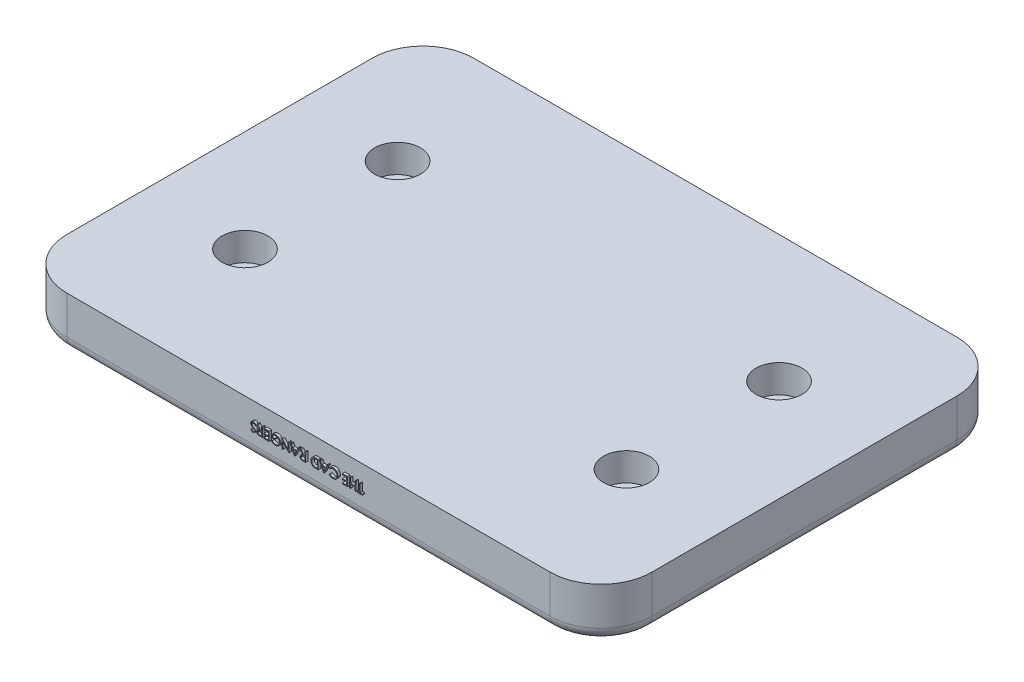
SolidWorks part; units mm, degrees
ref_plane "Front Plane" through (0, 0, 0) normal (0, 0, 1) x (1, 0, 0)
ref_plane "Top Plane" through (0, 0, 0) normal (0, 1, 0) x (1, 0, 0)
ref_plane "Right Plane" through (0, 0, 0) normal (1, 0, 0) x (0, 0, -1)
sketch "Sketch1" plane through (0, 0, 0) normal (0, 1, 0) x (1, 0, 0)
  line L0 (0, 125.2343) -> (0, -131.8583) construction
  line L1 (-95, -80) -> (95, -80)
  line L2 (-115, -60) -> (-115, 60)
  line L3 (-95, 80) -> (95, 80)
  line L4 (115, -60) -> (115, 60)
  line L5 (-115, -80) -> (115, 80) construction
  line L6 (-115, 80) -> (115, -80) construction
  line L7 (-168.0583, 0) -> (157.758, 0) construction
  arc A0 (95, 80) -> (115, 60) centre (95, 60) cw
  arc A1 (95, -80) -> (115, -60) centre (95, -60) ccw
  arc A2 (-95, -80) -> (-115, -60) centre (-95, -60) cw
  arc A3 (-115, 60) -> (-95, 80) centre (-95, 60) cw
  point P0 (0, 0)
  dimension "D3" = 20
  dimension "D1" = 160
  dimension "D2" = 230
extrude "Boss-Extrude1" add sketch "Sketch1" along normal blind 20
sketch "Sketch2" plane through (0, 0, 0) normal (0, -1, 0) x (1, 0, 0)
  line L0 (-115, 0) -> (138.7275, 0) construction
  line L1 (-115, -60) -> (-115, 60) construction
  line L3 (0, 55.4662) -> (0, -57.4516) construction
  circle A0 centre (-75, 30) radius 5.5
  circle A1 centre (75, 30) radius 5.5
  circle A2 centre (75, -30) radius 5.5
  circle A3 centre (-75, -30) radius 5.5
  dimension "D1" = 11
  dimension "D2" = 75
  dimension "D3" = 30
extrude "Cut-Extrude1" cut sketch "Sketch2" against normal blind 20
fillet "Fillet1" radius 5 8 edges at (109.1421, 0, -74.1421) (115, 0, 0) (109.1421, 0, 74.1421) (0, 0, 80) (-109.1421, 0, 74.1421) (-115, 0, 0) (-109.1421, 0, -74.1421) (0, 0, -80)
sketch "Sketch3" plane through (0, 20, 0) normal (0, 1, 0) x (1, 0, 0)
  circle A0 centre (-75, 30) radius 9
  circle A1 centre (-75, -30) radius 9
  circle A2 centre (75, 30) radius 9
  circle A3 centre (75, -30) radius 9
  dimension "D1" = 18
extrude "Cut-Extrude2" cut sketch "Sketch3" against normal blind 11
sketch "Sketch4" plane through (0, 0, 80) normal (0, 0, 1) x (1, 0, 0)
  line L0 (95, 13.7421) -> (-95, 13.7421) construction
  line L1 (95, 20) -> (95, 5) construction
  line L2 (-95, 20) -> (-95, 5) construction
  text T0 "THE CAD RANGERS"
extrude "Boss-Extrude2" add sketch "Sketch4" along normal blind 1
